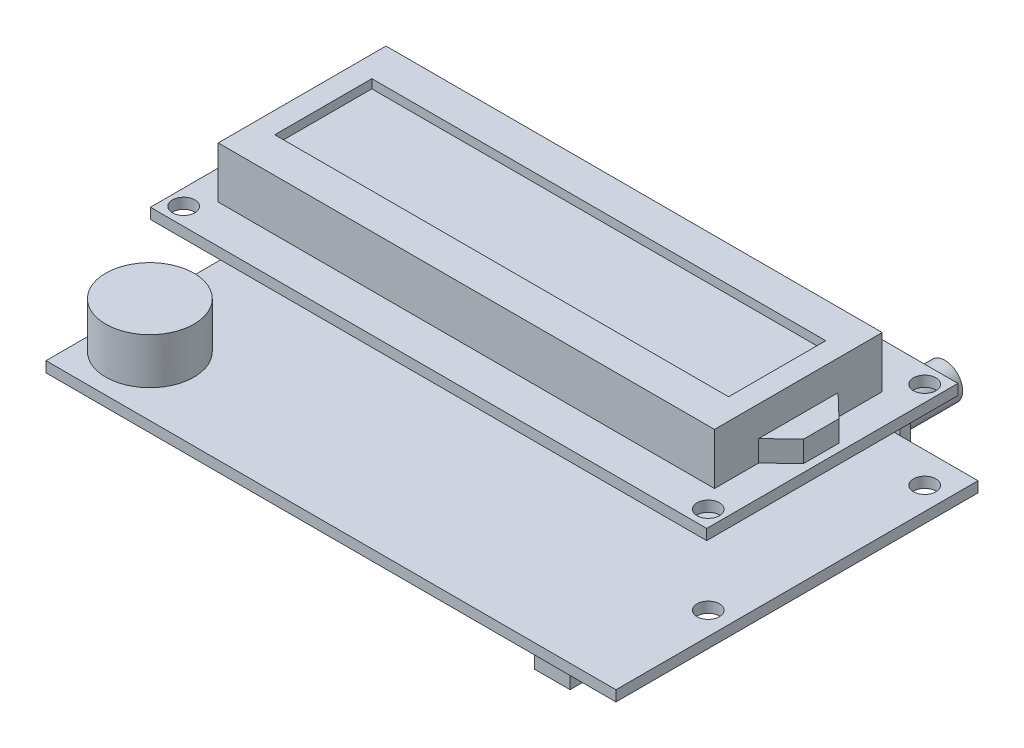
SolidWorks part; units mm, degrees
ref_plane "Front Plane" through (0, 0, 0) normal (0, 0, 1) x (1, 0, 0)
ref_plane "Top Plane" through (0, 0, 0) normal (0, 1, 0) x (1, 0, 0)
ref_plane "Right Plane" through (0, 0, 0) normal (1, 0, 0) x (0, 0, -1)
sketch "Sketch1" plane through (0, 0, 0) normal (0, 1, 0) x (1, 0, 0)
  line L0 (40.9892, 0) -> (40.9893, -52.07) construction
  line L1 (0, 0) -> (81.9785, 0)
  line L2 (0, 0) -> (0, -52.07)
  line L3 (0, -52.07) -> (81.9785, -52.07)
  line L4 (81.9785, 0) -> (81.9785, -52.07)
  circle A0 centre (3.2639, -4.4069) radius 1.6129
  circle A1 centre (3.2639, -35.5346) radius 1.6129
  circle A2 centre (78.7146, -35.5346) radius 1.6129
  circle A3 centre (78.7146, -4.4069) radius 1.6129
  point P15 (0, 0)
  point P16 (3.6549, -3.7988)
  point P17 (0, 0)
  point P18 (0, 0)
  point P19 (7.5505, -26.3255)
  point P20 (0, 0)
  dimension "D3" = 3.2258
  dimension "D1" = 52.07
  dimension "D2" = 81.9785
  dimension "D4" = 4.4069
  dimension "D5" = 3.2639
  dimension "D6" = 31.1277
extrude "Base PCB" add sketch "Sketch1" along normal blind 1.524
sketch "Sketch2" plane through (0, 0, 0) normal (0, 0, -1) x (-1, 0, 0)
  line L5 (-81.9785, 1.524) -> (-81.9785, 0) construction
  line L6 (-70.7517, -1.2192) -> (-64.4017, -1.2192)
  line L7 (-70.7517, -1.2192) -> (-70.7517, 5.1308)
  line L8 (-70.7517, 5.1308) -> (-64.4017, 5.1308)
  line L9 (-64.4017, -1.2192) -> (-64.4017, 5.1308)
  line L10 (-81.9785, 0) -> (0, 0) construction
  dimension "D1" = 6.35
  dimension "D2" = 11.2268
  dimension "D3" = 1.2192
extrude "Boss-Extrude2" add sketch "Sketch2" along normal blind 1.524
sketch "Sketch3" plane through (0, 0, -1.524) normal (0, 0, -1) x (-1, 0, 0)
  line L0 (-70.7517, 5.1308) -> (-64.4017, -1.2192) construction
  circle A0 centre (-67.5767, 1.9558) radius 2.54
  dimension "D1" = 5.08
extrude "Boss-Extrude3" add sketch "Sketch3" along normal blind 8.128
sketch "Sketch4" plane through (0, 1.524, 0) normal (0, 1, 0) x (1, 0, 0)
  line L0 (64.4017, 0) -> (0, 0) construction
  line L1 (6.9215, -2.9845) -> (48.0187, -2.9845)
  line L2 (6.9215, -2.9845) -> (6.9215, -5.5245)
  line L3 (6.9215, -5.5245) -> (48.0187, -5.5245)
  line L4 (48.0187, -2.9845) -> (48.0187, -5.5245)
  line L5 (0, 0) -> (0, -52.07) construction
  dimension "D1" = 41.0972
  dimension "D2" = 2.54
  dimension "D3" = 2.9845
  dimension "D4" = 6.9215
extrude "LCD Header" add sketch "Sketch4" along normal blind 11.0617
sketch "Sketch5" plane through (0, 12.5857, 0) normal (0, 1, 0) x (1, 0, 0)
  line L0 (3.2639, -4.4069) -> (0.9842, -4.4069) construction
  line L1 (0.9842, -1.905) -> (80.9942, -1.905)
  line L2 (0.9842, -1.905) -> (0.9842, -38.0365)
  line L3 (0.9842, -38.0365) -> (80.9942, -38.0365)
  line L4 (80.9942, -1.905) -> (80.9942, -38.0365)
  line L5 (3.2639, -4.4069) -> (3.2639, -1.905) construction
  line L6 (78.7146, -4.4069) -> (80.9942, -4.4069) construction
  line L7 (3.2639, -35.5346) -> (3.2639, -38.0365) construction
  circle A0 centre (78.7146, -4.4069) radius 1.6129 construction
  circle A1 centre (78.7146, -35.5346) radius 1.6129 construction
  circle A2 centre (3.2639, -35.5346) radius 1.6129 construction
  circle A3 centre (3.2639, -4.4069) radius 1.6129 construction
  circle A4 centre (78.7146, -4.4069) radius 1.6129
  circle A5 centre (78.7146, -35.5346) radius 1.6129
  circle A6 centre (3.2639, -35.5346) radius 1.6129
  circle A7 centre (3.2639, -4.4069) radius 1.6129
  point P16 (0, 0)
  point P21 (0, 0)
  dimension "D1" = 80.01
  dimension "D2" = 36.1315
extrude "LCD PCB" add sketch "Sketch5" along normal blind 1.524
sketch "Sketch6" plane through (0, 14.1097, 0) normal (0, 1, 0) x (1, 0, 0)
  line L0 (80.9942, -1.905) -> (0.9842, -1.905) construction
  line L1 (5.2133, -8.382) -> (76.5873, -8.382)
  line L2 (5.2133, -8.382) -> (5.2133, -32.512)
  line L3 (5.2133, -32.512) -> (76.5873, -32.512)
  line L4 (76.5873, -8.382) -> (76.5873, -32.512)
  line L5 (0.9842, -1.905) -> (0.9842, -38.0365) construction
  point P4 (5.6801, -7.5141)
  dimension "D1" = 71.374
  dimension "D2" = 24.13
  dimension "D3" = 6.477
  dimension "D4" = 4.2291
extrude "Boss-Extrude6" add sketch "Sketch6" along normal blind 7.366
sketch "Sketch7" plane through (0, 21.4757, 0) normal (0, 1, 0) x (1, 0, 0)
  line L0 (76.5873, -32.512) -> (76.5873, -8.382) construction
  line L1 (8.2613, -13.462) -> (73.5393, -13.462)
  line L2 (8.2613, -13.462) -> (8.2613, -27.432)
  line L3 (8.2613, -27.432) -> (73.5393, -27.432)
  line L4 (73.5393, -13.462) -> (73.5393, -27.432)
  line L5 (5.2133, -8.382) -> (5.2133, -32.512) construction
  line L6 (76.5873, -8.382) -> (5.2133, -8.382) construction
  line L7 (5.2133, -32.512) -> (76.5873, -32.512) construction
  dimension "D1" = 3.048
  dimension "D2" = 3.048
  dimension "D3" = 5.08
  dimension "D4" = 5.08
extrude "Cut-Extrude1" cut sketch "Sketch7" against normal blind 1.27
sketch "Sketch8" plane through (0, 14.1097, 0) normal (0, 1, 0) x (1, 0, 0)
  line L0 (76.5873, -14.732) -> (76.5873, -26.162)
  line L1 (76.5873, -32.512) -> (76.5873, -8.382) construction
  line L2 (76.5873, -26.162) -> (79.8893, -22.987)
  line L3 (79.8893, -22.987) -> (79.8893, -17.907)
  line L4 (79.8893, -17.907) -> (76.5873, -14.732)
  line L5 (79.8893, -20.447) -> (76.5873, -20.447) construction
  point P8 (0, 0)
  dimension "D1" = 11.43
  dimension "D2" = 5.08
  dimension "D3" = 3.302
extrude "Boss-Extrude7" add sketch "Sketch8" along normal blind 3.048
sketch "Sketch9" plane through (0, 1.524, 0) normal (0, 1, 0) x (1, 0, 0)
  line L0 (0, 0) -> (0, -52.07) construction
  line L1 (0, -52.07) -> (81.9785, -52.07) construction
  circle A0 centre (6.35, -43.4848) radius 6.35
  point P2 (6.2926, -46.6298)
  point P5 (6.35, -44.6172)
  dimension "D1" = 12.7
  dimension "D2" = 8.5852
extrude "Buzzer" add sketch "Sketch9" along normal blind 6.604
sketch "Sketch10" plane through (0, 0, 0) normal (0, -1, 0) x (1, 0, 0)
  line L0 (81.9785, 52.07) -> (81.9785, 0) construction
  line L1 (74.6125, 33.528) -> (69.5325, 33.528)
  line L2 (74.6125, 33.528) -> (74.6125, 51.308)
  line L3 (74.6125, 51.308) -> (69.5325, 51.308)
  line L4 (69.5325, 33.528) -> (69.5325, 51.308)
  line L5 (0, 52.07) -> (81.9785, 52.07) construction
  dimension "D1" = 5.08
  dimension "D2" = 17.78
  dimension "D3" = 7.366
  dimension "D4" = 0.762
extrude "Boss-Extrude9" add sketch "Sketch10" along normal blind 2.54
sketch "Sketch11" plane through (69.5325, 0, 0) normal (-1, 0, 0) x (0, 0, 1)
  line L0 (33.528, -1.27) -> (51.308, -1.27) construction
  line L5 (33.528, -2.54) -> (33.528, 0) construction
  line L6 (51.308, -2.54) -> (51.308, 0) construction
  line L7 (37.2745, -1.5875) -> (37.9095, -1.5875)
  line L8 (34.8615, -1.5875) -> (35.4965, -1.5875)
  line L9 (34.8615, -1.5875) -> (34.8615, -0.9525)
  line L10 (34.8615, -0.9525) -> (35.4965, -0.9525)
  line L11 (35.4965, -1.5875) -> (35.4965, -0.9525)
  line L12 (34.8615, -1.5875) -> (35.4965, -0.9525) construction
  line L13 (34.8615, -0.9525) -> (35.4965, -1.5875) construction
  line L14 (37.2745, -1.5875) -> (37.2745, -0.9525)
  line L15 (37.2745, -0.9525) -> (37.9095, -0.9525)
  line L16 (37.9095, -1.5875) -> (37.9095, -0.9525)
  line L17 (37.2745, -1.5875) -> (37.9095, -0.9525) construction
  line L18 (37.2745, -0.9525) -> (37.9095, -1.5875) construction
  line L19 (39.6875, -1.5875) -> (40.3225, -1.5875)
  line L20 (39.6875, -1.5875) -> (39.6875, -0.9525)
  line L21 (39.6875, -0.9525) -> (40.3225, -0.9525)
  line L22 (40.3225, -1.5875) -> (40.3225, -0.9525)
  line L23 (39.6875, -1.5875) -> (40.3225, -0.9525) construction
  line L24 (39.6875, -0.9525) -> (40.3225, -1.5875) construction
  line L25 (42.1005, -1.5875) -> (42.7355, -1.5875)
  line L26 (42.1005, -1.5875) -> (42.1005, -0.9525)
  line L27 (42.1005, -0.9525) -> (42.7355, -0.9525)
  line L28 (42.7355, -1.5875) -> (42.7355, -0.9525)
  line L29 (42.1005, -1.5875) -> (42.7355, -0.9525) construction
  line L30 (42.1005, -0.9525) -> (42.7355, -1.5875) construction
  line L31 (44.5135, -1.5875) -> (45.1485, -1.5875)
  line L32 (44.5135, -1.5875) -> (44.5135, -0.9525)
  line L33 (44.5135, -0.9525) -> (45.1485, -0.9525)
  line L34 (45.1485, -1.5875) -> (45.1485, -0.9525)
  line L35 (44.5135, -1.5875) -> (45.1485, -0.9525) construction
  line L36 (44.5135, -0.9525) -> (45.1485, -1.5875) construction
  line L37 (46.9265, -1.5875) -> (47.5615, -1.5875)
  line L38 (46.9265, -1.5875) -> (46.9265, -0.9525)
  line L39 (46.9265, -0.9525) -> (47.5615, -0.9525)
  line L40 (47.5615, -1.5875) -> (47.5615, -0.9525)
  line L41 (46.9265, -1.5875) -> (47.5615, -0.9525) construction
  line L42 (46.9265, -0.9525) -> (47.5615, -1.5875) construction
  line L43 (49.3395, -1.5875) -> (49.9745, -1.5875)
  line L44 (49.3395, -1.5875) -> (49.3395, -0.9525)
  line L45 (49.3395, -0.9525) -> (49.9745, -0.9525)
  line L46 (49.9745, -1.5875) -> (49.9745, -0.9525)
  line L47 (49.3395, -1.5875) -> (49.9745, -0.9525) construction
  line L48 (49.3395, -0.9525) -> (49.9745, -1.5875) construction
  line L49 (34.8615, -0.9525) -> (33.528, -0.9525) construction
  line L50 (49.9745, -0.9525) -> (51.308, -0.9525) construction
  point P6 (35.179, -1.27)
  point P11 (0, 0)
  point P12 (37.592, -1.27)
  point P17 (40.005, -1.27)
  point P22 (42.418, -1.27)
  point P27 (44.831, -1.27)
  point P32 (47.244, -1.27)
  point P37 (49.657, -1.27)
  dimension "D1" = 0.635
  dimension "D2" = 7
extrude "Boss-Extrude10" add sketch "Sketch11" along normal blind 6.35
sketch "Sketch12" plane through (0, 0, 0) normal (0, -1, 0) x (1, 0, 0)
  line L0 (0, 52.07) -> (81.9785, 52.07) construction
  line L1 (23.114, 42.926) -> (28.194, 42.926)
  line L2 (23.114, 42.926) -> (23.114, 35.814)
  line L3 (23.114, 35.814) -> (28.194, 35.814)
  line L4 (28.194, 42.926) -> (28.194, 35.814)
  line L5 (0, 0) -> (0, 52.07) construction
  dimension "D1" = 5.08
  dimension "D2" = 7.112
  dimension "D3" = 9.144
  dimension "D4" = 23.114
extrude "Boss-Extrude11" add sketch "Sketch12" along normal up to surface (2.54 mm away) up to face at (72.0725, -2.54, 42.418)
sketch "Sketch13" plane through (28.194, 0, 0) normal (1, 0, 0) x (0, 0, -1)
  line L0 (-42.926, -1.27) -> (-35.814, -1.27) construction
  line L1 (-42.926, -2.54) -> (-42.926, 0) construction
  line L2 (-35.814, -2.54) -> (-35.814, 0) construction
  line L3 (-39.6875, -1.5875) -> (-39.0525, -1.5875)
  line L4 (-42.1005, -1.5875) -> (-41.4655, -1.5875)
  line L5 (-42.1005, -1.5875) -> (-42.1005, -0.9525)
  line L6 (-42.1005, -0.9525) -> (-41.4655, -0.9525)
  line L7 (-41.4655, -1.5875) -> (-41.4655, -0.9525)
  line L8 (-42.1005, -1.5875) -> (-41.4655, -0.9525) construction
  line L9 (-42.1005, -0.9525) -> (-41.4655, -1.5875) construction
  line L10 (-39.6875, -1.5875) -> (-39.6875, -0.9525)
  line L11 (-39.6875, -0.9525) -> (-39.0525, -0.9525)
  line L12 (-39.0525, -1.5875) -> (-39.0525, -0.9525)
  line L13 (-39.6875, -1.5875) -> (-39.0525, -0.9525) construction
  line L14 (-39.6875, -0.9525) -> (-39.0525, -1.5875) construction
  line L15 (-37.2745, -1.5875) -> (-36.6395, -1.5875)
  line L16 (-37.2745, -1.5875) -> (-37.2745, -0.9525)
  line L17 (-37.2745, -0.9525) -> (-36.6395, -0.9525)
  line L18 (-36.6395, -1.5875) -> (-36.6395, -0.9525)
  line L19 (-37.2745, -1.5875) -> (-36.6395, -0.9525) construction
  line L20 (-37.2745, -0.9525) -> (-36.6395, -1.5875) construction
  line L21 (-42.1005, -0.9525) -> (-42.926, -0.9525) construction
  line L22 (-36.6395, -0.9525) -> (-35.814, -0.9525) construction
  point P6 (-41.783, -1.27)
  point P11 (-41.8135, -1.27)
  point P12 (-39.37, -1.27)
  point P17 (-36.957, -1.27)
  dimension "D1" = 0.635
  dimension "D2" = 3
extrude "Boss-Extrude12" add sketch "Sketch13" along normal blind 6.35
